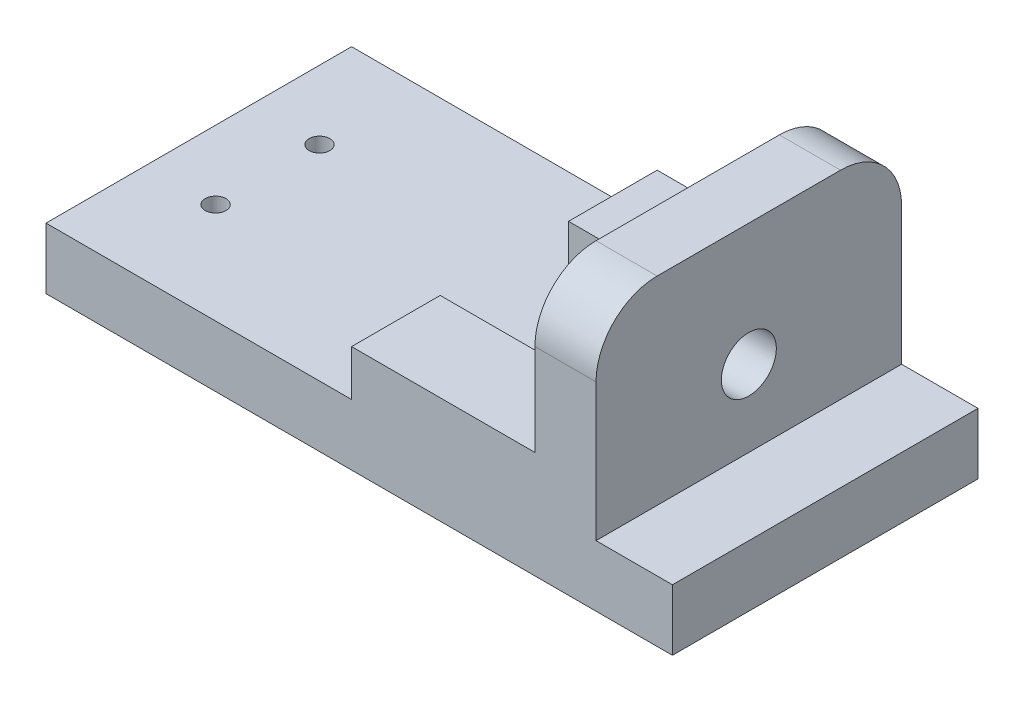
SolidWorks part; units mm, degrees
ref_plane "Front Plane" through (0, 0, 0) normal (0, 0, 1) x (1, 0, 0)
ref_plane "Top Plane" through (0, 0, 0) normal (0, 1, 0) x (1, 0, 0)
ref_plane "Right Plane" through (0, 0, 0) normal (1, 0, 0) x (0, 0, -1)
sketch "Sketch1" plane through (0, 0, 0) normal (0, 1, 0) x (1, 0, 0)
  line L1 (-102.5, -50) -> (102.5, -50)
  line L2 (-102.5, -50) -> (-102.5, 50)
  line L3 (-102.5, 50) -> (102.5, 50)
  line L4 (102.5, -50) -> (102.5, 50)
  line L5 (-102.5, -50) -> (102.5, 50) construction
  line L6 (-102.5, 50) -> (102.5, -50) construction
  point P0 (0, 0)
  dimension "D1" = 100
  dimension "D2" = 205
extrude "Boss-Extrude1" add sketch "Sketch1" along normal blind 20
sketch "Sketch2" plane through (0, 20, 0) normal (0, 1, 0) x (1, 0, 0)
  line L0 (-102.5, 50) -> (-102.5, -50) construction
  line L1 (-102.5, -50) -> (102.5, -50) construction
  line L2 (-102.5, 50) -> (-102.5, -50)
  line L3 (-102.5, -50) -> (102.5, -50)
  line L4 (-80, -17) -> (-80, 17) construction
  line L5 (-102.5, -50) -> (-80, -50)
  line L6 (-102.5, -50) -> (-102.5, -17)
  line L7 (-102.5, -17) -> (-80, -17) construction
  line L8 (-80, -50) -> (-80, -17) construction
  point P8 (-80, 17)
  point P9 (-80, -17)
  dimension "D1" = 33
  dimension "D2" = 22.5
  dimension "D3" = 34
hole_wizard "M8 Tapped Hole1" positions "3DSketch1" profile "Sketch3" tap size "M8" standard "ISO" end condition through all
sketch3d "3DSketch1"
  point P0 (-80, 20, -17)
  point P3 (-80, 20, 17)
sketch "Sketch3" plane through (-80, 20, -17) normal (1, 0, 0) x (0, 0, 1)
  line L0 (0, 0) -> (0, 20)
  line L1 (0, 20) -> (3.4, 20)
  line L2 (3.4, 20) -> (3.4, 0)
  line L5 (3.4, 0) -> (0, 0)
  line L11 (0, -6.35) -> (0, 107.95) construction
  dimension "Thru Tap Drill Dia." = 6.8
  dimension "Thru Tap Drill Depth" = 20
cosmetic thread "Hole Thread1" parameters "D2"=8
cosmetic thread "Hole Thread2" parameters "D2"=8
sketch "Sketch4" plane through (0, 20, 0) normal (0, 1, 0) x (1, 0, 0)
  line L0 (0, 0) -> (126.348, 0) construction
  line L1 (-102.5, -50) -> (102.5, -50) construction
  line L2 (57.5, -50) -> (-2.5, -50)
  line L3 (57.5, -50) -> (57.5, -21)
  line L4 (57.5, -21) -> (-2.5, -21)
  line L5 (-2.5, -50) -> (-2.5, -21)
  line L6 (102.5, -50) -> (102.5, 50) construction
  line L7 (-2.5, 50) -> (-2.5, 21)
  line L8 (57.5, 21) -> (-2.5, 21)
  line L9 (57.5, 50) -> (57.5, 21)
  line L10 (57.5, 50) -> (-2.5, 50)
  dimension "D1" = 60
  dimension "D2" = 29
  dimension "D3" = 45
extrude "Boss-Extrude2" add sketch "Sketch4" along normal blind 15
sketch "Sketch5" plane through (0, 20, 0) normal (0, 1, 0) x (1, 0, 0)
  line L0 (57.5, -50) -> (102.5, -50) construction
  line L1 (57.5, 50) -> (77.5, 50)
  line L2 (57.5, 50) -> (57.5, -50)
  line L3 (57.5, -50) -> (77.5, -50)
  line L4 (77.5, 50) -> (77.5, -50)
  dimension "D1" = 20
extrude "Boss-Extrude3" add sketch "Sketch5" along normal blind 65
fillet "Fillet1" radius 20 2 edges at (67.5, 85, 50) (67.5, 85, -50)
sketch "Sketch6" plane through (57.5, 0, 0) normal (-1, 0, 0) x (0, 0, 1)
  line L0 (-30, 85) -> (30, 85) construction
  line L1 (-21, 20) -> (21, 20)
  line L2 (-21, 20) -> (-21, 85)
  line L3 (-21, 85) -> (21, 85)
  line L4 (21, 20) -> (21, 85)
  line L5 (21, 35) -> (21, 20) construction
  line L6 (0, 20) -> (0, 45)
  point P13 (0, 45)
  dimension "D1" = 25
hole_wizard "Ø18.0 (18) Diameter Hole1" positions "3DSketch3" profile "Sketch8" hole size "Ø18.0" standard "ISO" end condition through all
sketch3d "3DSketch3"
  point P0 (57.5, 45, 0)
sketch "Sketch8" plane through (57.5, 45, 0) normal (0, 1, 0) x (0, 0, 1)
  line L0 (0, 0) -> (0, 45)
  line L1 (0, 45) -> (9, 45)
  line L2 (9, 45) -> (9, 0)
  line L5 (9, 0) -> (0, 0)
  line L11 (0, -6.35) -> (0, 107.95) construction
  dimension "Thru Hole Dia." = 18
  dimension "Thru Hole Depth" = 45
